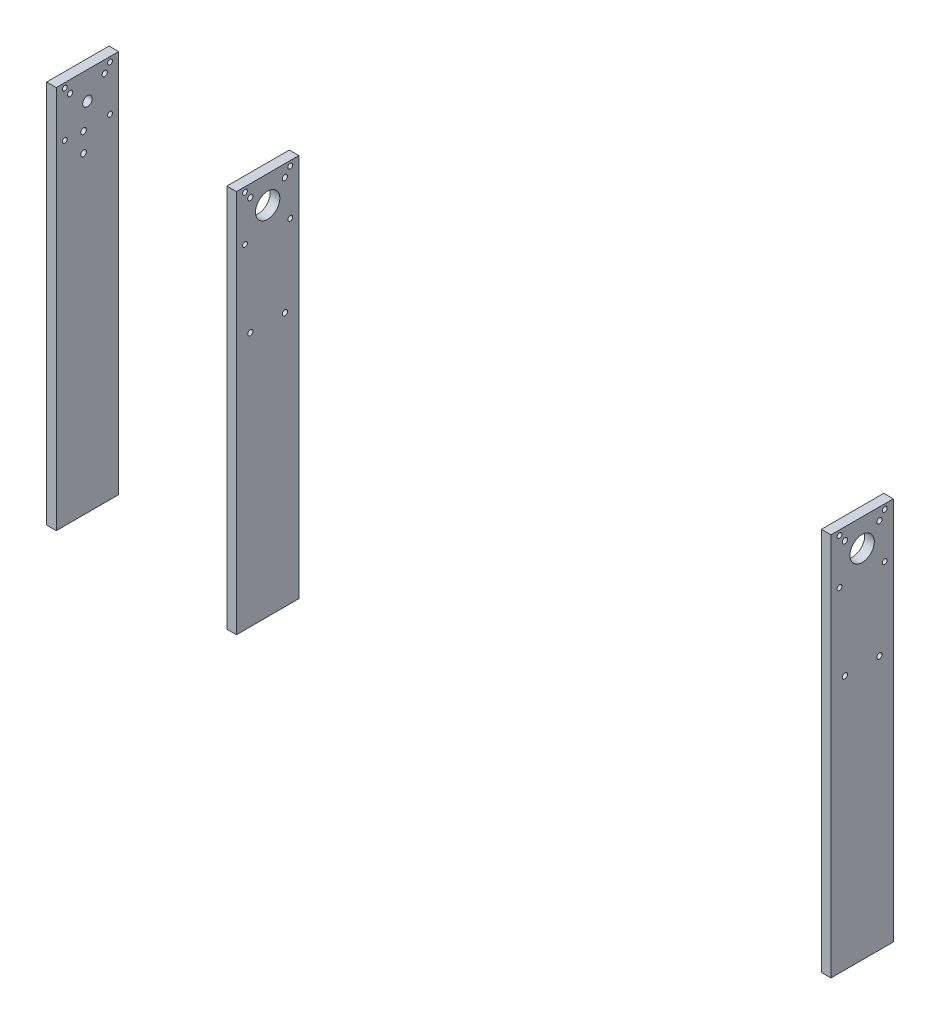
SolidWorks part; units mm, degrees
ref_plane "Front Plane" through (0, 0, 0) normal (0, 0, 1) x (1, 0, 0)
ref_plane "Top Plane" through (0, 0, 0) normal (0, 1, 0) x (1, 0, 0)
ref_plane "Right Plane" through (0, 0, 0) normal (1, 0, 0) x (0, 0, -1)
sketch "Sketch1" plane through (0, 0, 0) normal (1, 0, 0) x (0, 0, -1)
  line L0 (0, -106) -> (0, -123.4646) construction
  line L1 (0, 28.575) -> (0, -371.425) construction
  line L8 (23.5712, -23.5712) -> (-23.5712, -23.5712) construction
  line L9 (23.5712, -23.5712) -> (23.5712, 23.5712) construction
  line L10 (23.5712, 23.5712) -> (-23.5712, 23.5712) construction
  line L11 (-23.5712, -23.5712) -> (-23.5712, 23.5712) construction
  line L12 (23.5712, -23.5712) -> (-23.5712, 23.5712) construction
  line L13 (23.5712, 23.5712) -> (-23.5712, -23.5712) construction
  line L15 (-32.5, -371.425) -> (32.5, -371.425)
  line L16 (-32.5, -371.425) -> (-32.5, 28.575)
  line L17 (-32.5, 28.575) -> (32.5, 28.575)
  line L18 (32.5, -371.425) -> (32.5, 28.575)
  line L19 (-32.5, -371.425) -> (32.5, 28.575) construction
  line L20 (-32.5, 28.575) -> (32.5, -371.425) construction
  circle A0 centre (-23.5712, 23.5712) radius 2.54
  circle A1 centre (23.5712, 23.5712) radius 2.54
  circle A2 centre (23.5712, -23.5712) radius 2.54
  circle A3 centre (-23.5712, -23.5712) radius 2.54
  circle A8 centre (0, 0) radius 12.7
  circle A9 centre (18, 16) radius 2.75
  circle A10 centre (0, 16) radius 18 construction
  circle A11 centre (-18, 16) radius 2.75
  circle A12 centre (18, -106) radius 2.75
  circle A13 centre (-18, -106) radius 2.75
  point P0 (0, 0)
  point P8 (0, 0)
  point P37 (0, -171.425)
  dimension "D5" = 5.08
  dimension "D8" = 5.5
  dimension "D9" = 400
  dimension "D2" = 25.4
  dimension "D3" = 47.1424
  dimension "D4" = 47.1424
  dimension "D10" = 65
ref_plane "Plane1" through (609.6, 0, 0) normal (1, 0, 0) x (0, 0, -1)
sketch "Sketch4" plane through (0, 0, 0) normal (0, 0, 1) x (1, 0, 0)
  line L0 (0, 0) -> (609.6, 0) construction
extrude "Boss-Extrude1" add sketch "Sketch1" against normal blind 10
ref_plane "Plane2" through (0, 0, 0) normal (1, 0, 0) x (0, 0, -1)
ref_plane "Plane3" through (-187.8, 0, 0) normal (-1, 0, 0) x (0, 0, 1)
ref_plane "Plane4" through (0, 0, 159.5) normal (0, 0, 1) x (1, 0, 0)
sketch "Sketch15" plane through (-187.8, 0, 0) normal (-1, 0, 0) x (0, 0, 1)
  line L1 (0, 28.575) -> (0, -371.425) construction
  line L9 (23.5712, -23.5712) -> (23.5712, 23.5712) construction
  line L10 (23.5712, 23.5712) -> (-23.5712, 23.5712) construction
  line L11 (-23.5712, -23.5712) -> (-23.5712, 23.5712) construction
  line L12 (23.5712, -23.5712) -> (-23.5712, 23.5712) construction
  line L13 (23.5712, 23.5712) -> (-23.5712, -23.5712) construction
  line L15 (-32.5, -371.425) -> (32.5, -371.425)
  line L16 (-32.5, -371.425) -> (-32.5, 28.575)
  line L17 (-32.5, 28.575) -> (32.5, 28.575)
  line L18 (32.5, -371.425) -> (32.5, 28.575)
  line L19 (-32.5, -371.425) -> (32.5, 28.575) construction
  line L20 (-32.5, 28.575) -> (32.5, -371.425) construction
  circle A0 centre (-23.5712, 23.5712) radius 2.54
  circle A1 centre (23.5712, 23.5712) radius 2.54
  circle A2 centre (-23.5712, -23.5712) radius 2.54
  circle A3 centre (23.5712, -23.5712) radius 2.54
  circle A4 centre (4, -25) radius 3
  circle A6 centre (4, -45) radius 3
  circle A8 centre (0, 0) radius 5
  circle A9 centre (18, 16) radius 2.75
  circle A10 centre (0, 16) radius 18 construction
  circle A11 centre (-18, 16) radius 2.75
  point P0 (0, 0)
  point P8 (0, 0)
  point P37 (0, -171.425)
  dimension "D5" = 5.08
  dimension "D8" = 5.5
  dimension "D9" = 400
  dimension "D2" = 10
  dimension "D3" = 47.1424
  dimension "D10" = 65
extrude "Boss-Extrude11" add sketch "Sketch15" along normal blind 10 separate body
sketch "Sketch16" plane through (609.6, 0, 0) normal (1, 0, 0) x (0, 0, -1)
  line L0 (0, -106) -> (0, -123.4646) construction
  line L1 (0, 28.575) -> (0, -371.425) construction
  line L8 (23.5712, -23.5712) -> (-23.5712, -23.5712) construction
  line L9 (23.5712, -23.5712) -> (23.5712, 23.5712) construction
  line L10 (23.5712, 23.5712) -> (-23.5712, 23.5712) construction
  line L11 (-23.5712, -23.5712) -> (-23.5712, 23.5712) construction
  line L12 (23.5712, -23.5712) -> (-23.5712, 23.5712) construction
  line L13 (23.5712, 23.5712) -> (-23.5712, -23.5712) construction
  line L15 (-32.5, -371.425) -> (32.5, -371.425)
  line L16 (-32.5, -371.425) -> (-32.5, 28.575)
  line L17 (-32.5, 28.575) -> (32.5, 28.575)
  line L18 (32.5, -371.425) -> (32.5, 28.575)
  line L19 (-32.5, -371.425) -> (32.5, 28.575) construction
  line L20 (-32.5, 28.575) -> (32.5, -371.425) construction
  circle A0 centre (-23.5712, 23.5712) radius 2.54
  circle A1 centre (23.5712, 23.5712) radius 2.54
  circle A2 centre (23.5712, -23.5712) radius 2.54
  circle A3 centre (-23.5712, -23.5712) radius 2.54
  circle A8 centre (0, 0) radius 12.7
  circle A9 centre (18, 16) radius 2.75
  circle A10 centre (0, 16) radius 18 construction
  circle A11 centre (-18, 16) radius 2.75
  circle A12 centre (18, -106) radius 2.75
  circle A13 centre (-18, -106) radius 2.75
  point P0 (0, 0)
  point P8 (0, 0)
  point P37 (0, -171.425)
  dimension "D5" = 5.08
  dimension "D8" = 5.5
  dimension "D9" = 400
  dimension "D2" = 25.4
  dimension "D3" = 47.1424
  dimension "D4" = 47.1424
  dimension "D10" = 65
extrude "Boss-Extrude12" add sketch "Sketch16" along normal blind 10 separate body
